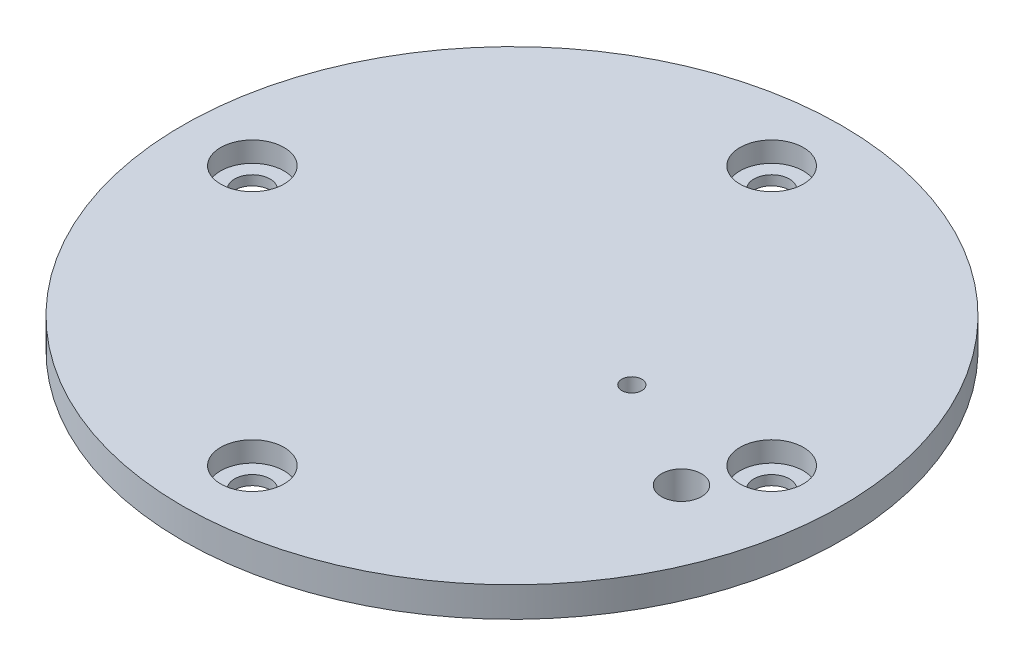
SolidWorks part; units mm, degrees
material "6061-T6 (SS)"
ref_plane "Front Plane" through (0, 0, 0) normal (0, 0, 1) x (1, 0, 0)
ref_plane "Top Plane" through (0, 0, 0) normal (0, 1, 0) x (1, 0, 0)
ref_plane "Right Plane" through (0, 0, 0) normal (1, 0, 0) x (0, 0, -1)
sketch "Sketch1" plane through (0, 0, 0) normal (0, 1, 0) x (1, 0, 0)
  circle A0 centre (0, 0) radius 16.5
  dimension "D1" = 33
extrude "Boss-Extrude1" add sketch "Sketch1" along normal blind 1.5
sketch "Sketch3" plane through (0, 1.5, 0) normal (0, 1, 0) x (1, 0, 0)
  circle A0 centre (0, -10.25) radius 0.25
  circle A1 centre (0, 0) radius 9.8
  dimension "D1" = 0.5
  dimension "D2" = 10.25
  dimension "D3" = 19.6
sketch "Sketch4" plane through (0, 1.5, 0) normal (0, -1, 0) x (1, 0, 0)
  line L0 (0, 0) -> (13.2597, 13.2597) construction
  circle A0 centre (7.7782, 7.7782) radius 1
  dimension "D2" = 2
  dimension "D1" = 11
sketch "Sketch5" plane through (0, 1.5, 0) normal (0, 1, 0) x (1, 0, 0)
  circle A0 centre (0, 0) radius 11
  dimension "D1" = 22
hole_wizard "CBORE for #0 Socket Head Cap Screw1" positions "Sketch6" profile "Sketch7" counterbore size "#0" standard "ANSI Inch" end condition through all
sketch "Sketch6" plane through (0, 1.5, 0) normal (0, 1, 0) x (1, 0, 0)
  point P0 (13, 0)
  dimension "D1" = 13
sketch "Sketch7" plane through (13, 1.5, 0) normal (1, 0, 0) x (0, 0, 1)
  line L0 (0, 0) -> (0, 1.5)
  line L1 (0, 1.5) -> (0.889, 1.5)
  line L3 (0.889, 1.5) -> (0.889, 1.016)
  line L4 (0.889, 1.016) -> (1.5875, 1.016)
  line L5 (1.5875, 1.016) -> (1.5875, 0)
  line L7 (1.5875, 0) -> (0, 0)
  line L11 (0, -6.35) -> (0, 107.95) construction
  dimension "Thru Hole Dia." = 1.778
  dimension "Thru Hole Depth" = 1.5
  dimension "C'Bore Dia." = 3.175
  dimension "C'Bore Depth" = 1.016
pattern_circular "CirPattern1" count 4 over 360 about axis through (0, 0, 0) along (0, 1, 0) of "CBORE for #0 Socket Head Cap Screw1"
sketch "Sketch8" plane through (0, 0, 0) normal (0, -1, 0) x (1, 0, 0)
  circle A0 centre (6, 0) radius 0.5
  dimension "D1" = 1
  dimension "D2" = 6
extrude "Cut-Extrude1" cut sketch "Sketch8" against normal blind 1.5
sketch "Sketch9" plane through (0, 1.5, 0) normal (0, 1, 0) x (1, 0, 0)
  line L0 (13, 0) -> (0, 0) construction
  line L1 (0, 0) -> (11.5911, -3.1058) construction
  circle A0 centre (11.5911, -3.1058) radius 1
  dimension "D1" = 2
  dimension "D2" = 12
  dimension "D3" = 15
extrude "Cut-Extrude2" cut sketch "Sketch9" against normal blind 10
